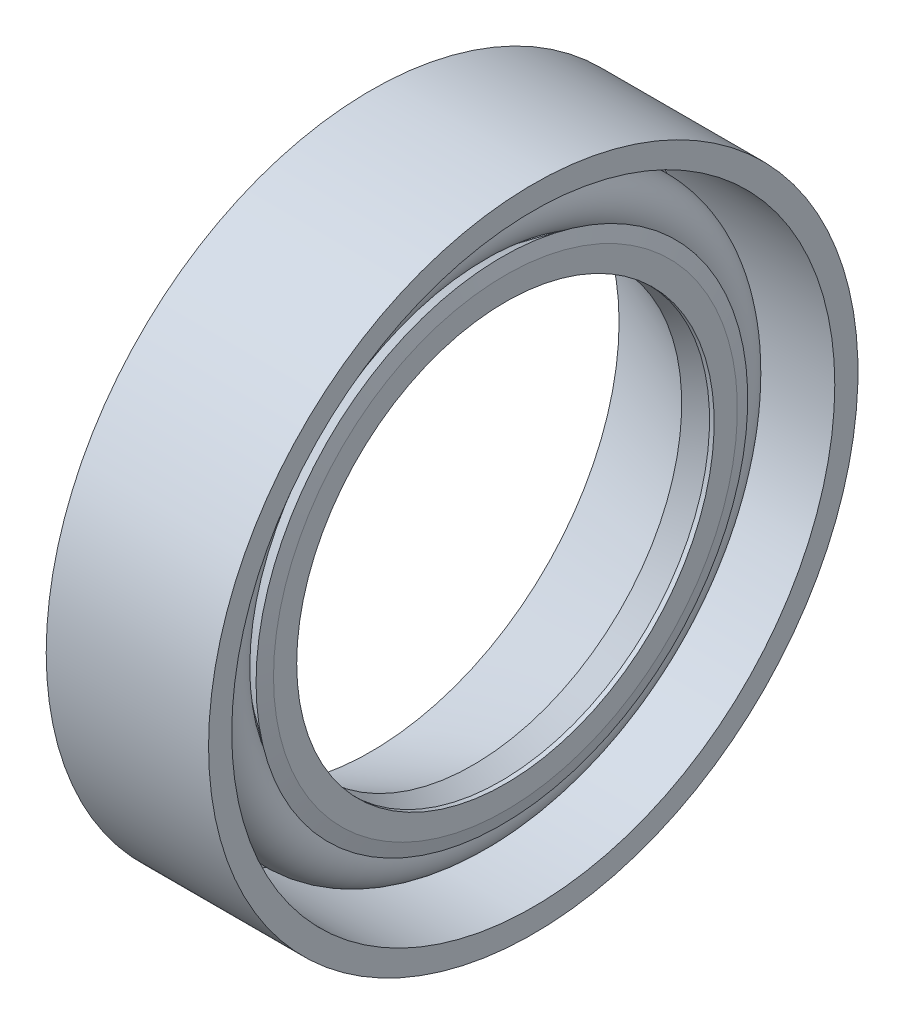
SolidWorks part; units mm, degrees
material "Rubber"
ref_plane "Plan de face" through (0, 0, 0) normal (0, 0, 1) x (1, 0, 0)
ref_plane "Plan de dessus" through (0, 0, 0) normal (0, 1, 0) x (1, 0, 0)
ref_plane "Plan de droite" through (0, 0, 0) normal (1, 0, 0) x (0, 0, -1)
sketch "Sketch1" plane through (0, 0, 0) normal (0, 0, 1) x (1, 0, 0)
  line L0 (0, 7) -> (3.5, 7)
  line L1 (0, 7) -> (0, 0) construction
  line L2 (3.5, 7) -> (3.5, 6.5)
  line L3 (3.5, 6.5) -> (0.5, 6.5)
  line L4 (0, 7) -> (0, 5.35)
  line L5 (0.5, 6.5) -> (0.5, 5.5)
  line L6 (0, 4.5) -> (3.5, 4.5) construction
  line L7 (0, 5.35) -> (2.2, 4.5)
  line L8 (2.2, 4.5) -> (2.8, 4.9286)
  line L10 (2.1727, 4.835) -> (1.9772, 4.9127)
  line L11 (2.1727, 4.835) -> (2.8236, 5.3)
  line L12 (2.8236, 5.3) -> (2.9, 5)
  line L13 (3.5, 4.5) -> (3.5, 7) construction
  line L14 (0, 0) -> (3.7853, 0) construction
  line L15 (1.6917, 5.0262) -> (0.5, 5.5)
  line L16 (2.9, 5) -> (2.9, 4.5)
  line L17 (2.8, 4.5) -> (2.8, 4.9286)
  line L18 (2.8, 4.5) -> (2.9, 4.5)
  arc A0 (1.9772, 4.9127) -> (1.6917, 5.0262) centre (2.0488, 5.5084) ccw
  dimension "D15" = 1.2
  dimension "D16" = 0.58
  dimension "D17" = 0.62
  dimension "D1" = 7
  dimension "D2" = 3.5
  dimension "D3" = 0.5
  dimension "D4" = 3
  dimension "D5" = 1.65
  dimension "D6" = 1
  dimension "D7" = 2.5
  dimension "D8" = 3.5
  dimension "D9" = 0.3096
  dimension "D10" = 2.3585
  dimension "D11" = 2.8236
  dimension "D12" = 0.8
  dimension "D13" = 1.8
  dimension "D14" = 0.8602
  dimension "D18" = 0.1
  dimension "D19" = 0.7373
revolve "Revolve5" add sketch "Sketch1" angle 360 about L14
